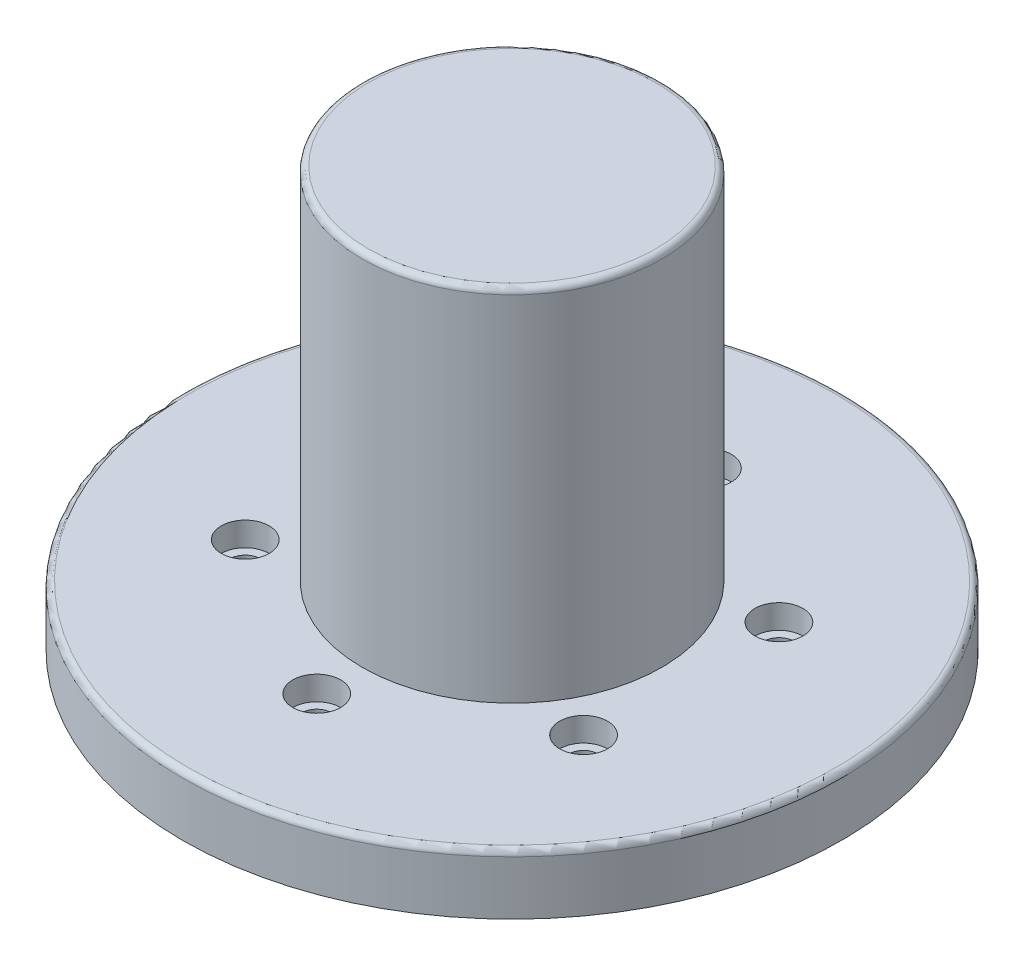
SolidWorks part; units mm, degrees
ref_plane "Front Plane" through (0, 0, 0) normal (0, 0, 1) x (1, 0, 0)
ref_plane "Top Plane" through (0, 0, 0) normal (0, 1, 0) x (1, 0, 0)
ref_plane "Right Plane" through (0, 0, 0) normal (1, 0, 0) x (0, 0, -1)
sketch "Sketch1" plane through (0, 0, 0) normal (0, 1, 0) x (1, 0, 0)
  line L0 (0, 0) -> (-28230.2161, 0) construction
  line L1 (0, 0) -> (0, -28230.2161) construction
  circle A0 centre (0, 0) radius 27.5
  dimension "D1" = 55
extrude "Boss-Extrude1" add sketch "Sketch1" along normal blind 5
sketch "Sketch2" plane through (0, 5, 0) normal (0, 1, 0) x (1, 0, 0)
  line L0 (0, 0) -> (-50000, 0) construction
  line L1 (0, 0) -> (0, -50000) construction
  circle A0 centre (0, 0) radius 16.3 construction
  circle A1 centre (0, 16.3) radius 2
  circle A2 centre (14.1162, 8.15) radius 2
  circle A3 centre (14.1162, -8.15) radius 2
  circle A4 centre (0, -16.3) radius 2
  circle A5 centre (-14.1162, -8.15) radius 2
  circle A6 centre (-14.1162, 8.15) radius 2
  point P22 (0, 0)
  dimension "D1" = 32.6
  dimension "D2" = 4
extrude "Cut-Extrude1" cut sketch "Sketch2" against normal blind 2
sketch "Sketch3" plane through (0, 5, 0) normal (0, 1, 0) x (1, 0, 0)
  line L0 (0, 0) -> (-50000, 0) construction
  line L1 (0, 0) -> (0, -50000) construction
  circle A0 centre (0, 16.3) radius 1.25
  circle A1 centre (14.1162, 8.15) radius 1.25
  circle A2 centre (14.1162, -8.15) radius 1.25
  circle A3 centre (0, -16.3) radius 1.25
  circle A4 centre (-14.1162, -8.15) radius 1.25
  circle A5 centre (-14.1162, 8.15) radius 1.25
  point P21 (0, 0)
  dimension "D1" = 2.5
extrude "Cut-Extrude2" cut sketch "Sketch3" against normal through all
sketch "Sketch4" plane through (0, 0, 0) normal (0, -1, 0) x (1, 0, 0)
  line L0 (0, 0) -> (-50000, 0) construction
  line L1 (0, 0) -> (0, -50000) construction
  line L2 (12.1162, 6.9953) -> (14.1162, 5.8406)
  line L3 (0, 13.9906) -> (2, 15.1453)
  line L4 (2, 15.1453) -> (2, 17.4547)
  line L5 (2, 17.4547) -> (0, 18.6094)
  line L6 (0, 18.6094) -> (-2, 17.4547)
  line L7 (-2, 17.4547) -> (-2, 15.1453)
  line L8 (-2, 15.1453) -> (0, 13.9906)
  line L9 (14.1162, 5.8406) -> (16.1162, 6.9953)
  line L10 (16.1162, 6.9953) -> (16.1162, 9.3047)
  line L11 (16.1162, 9.3047) -> (14.1162, 10.4594)
  line L12 (14.1162, 10.4594) -> (12.1162, 9.3047)
  line L13 (12.1162, 9.3047) -> (12.1162, 6.9953)
  line L14 (12.1162, -6.9953) -> (12.1162, -9.3047)
  line L15 (12.1162, -9.3047) -> (14.1162, -10.4594)
  line L16 (14.1162, -10.4594) -> (16.1162, -9.3047)
  line L17 (16.1162, -9.3047) -> (16.1162, -6.9953)
  line L18 (16.1162, -6.9953) -> (14.1162, -5.8406)
  line L19 (14.1162, -5.8406) -> (12.1162, -6.9953)
  line L20 (0, -13.9906) -> (-2, -15.1453)
  line L21 (-2, -15.1453) -> (-2, -17.4547)
  line L22 (-2, -17.4547) -> (0, -18.6094)
  line L23 (0, -18.6094) -> (2, -17.4547)
  line L24 (2, -17.4547) -> (2, -15.1453)
  line L25 (2, -15.1453) -> (0, -13.9906)
  line L26 (-12.1162, -6.9953) -> (-14.1162, -5.8406)
  line L27 (-14.1162, -5.8406) -> (-16.1162, -6.9953)
  line L28 (-16.1162, -6.9953) -> (-16.1162, -9.3047)
  line L29 (-16.1162, -9.3047) -> (-14.1162, -10.4594)
  line L30 (-14.1162, -10.4594) -> (-12.1162, -9.3047)
  line L31 (-12.1162, -9.3047) -> (-12.1162, -6.9953)
  line L32 (-12.1162, 6.9953) -> (-12.1162, 9.3047)
  line L33 (-12.1162, 9.3047) -> (-14.1162, 10.4594)
  line L34 (-14.1162, 10.4594) -> (-16.1162, 9.3047)
  line L35 (-16.1162, 9.3047) -> (-16.1162, 6.9953)
  line L36 (-16.1162, 6.9953) -> (-14.1162, 5.8406)
  line L37 (-14.1162, 5.8406) -> (-12.1162, 6.9953)
  circle A0 centre (0, 16.3) radius 2 construction
  circle A1 centre (14.1162, 8.15) radius 2 construction
  circle A2 centre (14.1162, -8.15) radius 2 construction
  circle A3 centre (0, -16.3) radius 2 construction
  circle A4 centre (-14.1162, -8.15) radius 2 construction
  circle A5 centre (-14.1162, 8.15) radius 2 construction
  point P57 (0, 0)
  dimension "D1" = 4
extrude "Cut-Extrude3" cut sketch "Sketch4" against normal blind 1.7
sketch "Sketch5" plane through (0, 5, 0) normal (0, 1, 0) x (1, 0, 0)
  line L0 (0, 0) -> (-50000, 0) construction
  line L1 (0, 0) -> (0, -50000) construction
  circle A0 centre (0, 0) radius 12.5
  dimension "D1" = 25
extrude "Boss-Extrude2" add sketch "Sketch5" along normal blind 30
fillet "Fillet1" radius 0.5 2 edges at (0, 5, 27.5) (0, 35, 12.5)
